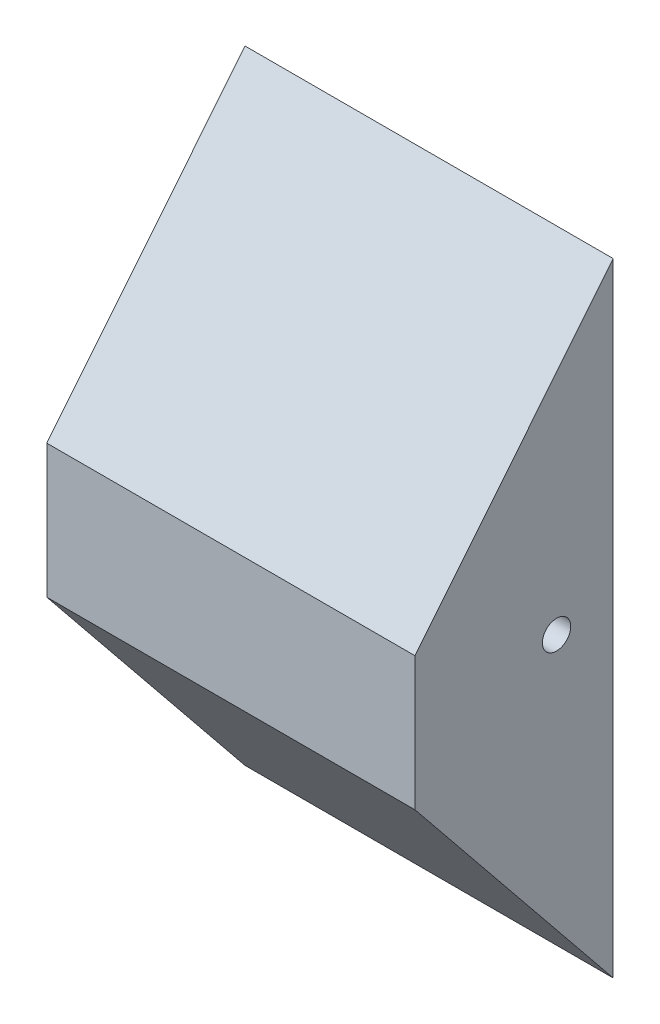
SolidWorks part; units mm, degrees
ref_plane "Ön Düzlem" through (0, 0, 0) normal (0, 0, 1) x (1, 0, 0)
ref_plane "Üst Düzlem" through (0, 0, 0) normal (0, 1, 0) x (1, 0, 0)
ref_plane "Sağ Düzlem" through (0, 0, 0) normal (1, 0, 0) x (0, 0, -1)
sketch "Çizim1" plane through (0, 0, 0) normal (0, 0, 1) x (1, 0, 0)
  line L1 (-6.5, 11) -> (6.5, 11)
  line L2 (-6.5, 11) -> (-6.5, -11)
  line L3 (-6.5, -11) -> (6.5, -11)
  line L4 (6.5, 11) -> (6.5, -11)
  line L5 (-6.5, 11) -> (6.5, -11) construction
  line L6 (-6.5, -11) -> (6.5, 11) construction
  point P0 (0, 0)
  dimension "D1" = 13
  dimension "D2" = 22
extrude "Yükseklik-Ekstrüzyon1" add sketch "Çizim1" along normal blind 7
sketch "Çizim2" plane through (6.5, 0, 0) normal (1, 0, 0) x (0, 0, -1)
  line L0 (0, 11) -> (-7, 2.3557)
  line L1 (-7, -11) -> (-7, 11) construction
  line L2 (0, -11) -> (-7, -2.3557)
  line L3 (-7, 11) -> (0, 11) construction
  line L4 (-7, -11) -> (0, -11) construction
  line L5 (-7, 2.3557) -> (-7, -2.3557)
  line L6 (0, 11) -> (-7, 11)
  line L7 (-7, 11) -> (-7, 2.3557)
  line L8 (-7, -2.3557) -> (-7, -11)
  line L9 (-7, -11) -> (0, -11)
  line M4 (0, 11) -> (-7, 11)
  line M5 (-7, 11) -> (-7, -11)
  line M6 (-7, -11) -> (0, -11)
  dimension "D1" = 51
  dimension "D2" = 51
extrude "Kes-Ekstrüzyon1" cut sketch "Çizim2" against normal through all contours L0 M4 M5 | L2 M6 M5
sketch "Çizim3" plane through (0, 0, 0) normal (0, 0, -1) x (-1, 0, 0)
  line L0 (-6.5, 0) -> (6.5, 0)
  line L1 (-6.5, -11) -> (-6.5, 11) construction
  line L2 (6.5, 11) -> (6.5, -11) construction
  line L3 (6.5, -11) -> (-6.5, -11) construction
  line L4 (-0.2918, 8.4514) -> (0.2918, 8.4514)
  line L5 (-0.2918, 8.4514) -> (-0.2918, 3.5486)
  line L6 (-0.2918, 3.5486) -> (0.2918, 3.5486)
  line L7 (0.2918, 8.4514) -> (0.2918, 3.5486)
  line L8 (-0.2918, 8.4514) -> (0.2918, 3.5486) construction
  line L9 (-0.2918, 3.5486) -> (0.2918, 8.4514) construction
  line L10 (-6.5, 11) -> (6.5, 11) construction
  circle A0 centre (0, -6) radius 2.271
  point P8 (0, 6)
  dimension "D1" = 5
  dimension "D2" = 5
extrude "Yükseklik-Ekstrüzyon2" add sketch "Çizim3" along normal blind 0.5 contours L7 L4 L5 L6 | A0
sketch "Çizim4" plane through (0, 0, -0.5) normal (0, 0, -1) x (-1, 0, 0)
  circle A1 centre (0, -6) radius 1.9239
extrude "Kes-Ekstrüzyon2" cut sketch "Çizim4" against normal blind 0.5
sketch "Çizim5" plane through (6.5, 0, 0) normal (1, 0, 0) x (0, 0, -1)
  line L0 (0, -11) -> (0, 0.5)
  line L1 (0, -11) -> (0, 11) construction
  line L3 (-7, 0.5) -> (-2, 0.5)
  line L4 (-7, -2.3557) -> (-7, 2.3557) construction
  circle A0 centre (-2, 0.5) radius 0.5
  dimension "D3" = 1
  dimension "D1" = 11.5
  dimension "D2" = 5
extrude "Kes-Ekstrüzyon3" cut sketch "Çizim5" against normal through all
